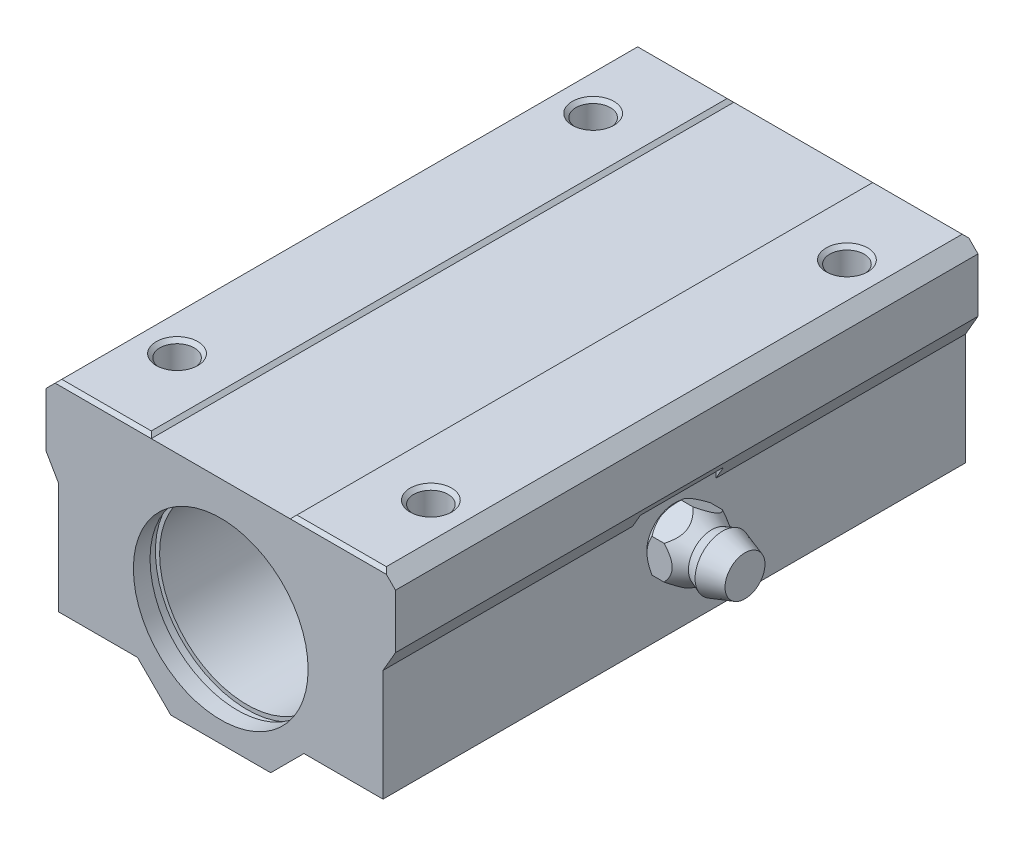
SolidWorks part; units mm, degrees
material "Plain Carbon Steel"
ref_plane "Front Plane" through (0, 0, 0) normal (0, 0, 1) x (1, 0, 0)
ref_plane "Top Plane" through (0, 0, 0) normal (0, 1, 0) x (1, 0, 0)
ref_plane "Right Plane" through (0, 0, 0) normal (1, 0, 0) x (0, 0, -1)
ref_plane "Plane1" through (0, 0, 0) normal (0, 0, 1) x (1, 0, 0)
sketch "Sketch1" plane through (0, 0, 0) normal (0, 0, 1) x (1, 0, 0)
  line L0 (-21, 12.5) -> (-21, 6)
  line L1 (-21, 6) -> (-19.5, 3.4019)
  line L2 (-19.5, 3.4019) -> (-19.5, -10)
  line L3 (-19.5, -10) -> (-10, -10)
  line L4 (-10, -10) -> (-6, -14)
  line L5 (-6, -14) -> (6, -14)
  line L6 (6, -14) -> (10, -10)
  line L7 (10, -10) -> (19.5, -10)
  line L8 (19.5, -10) -> (19.5, 3.4019)
  line L9 (19.5, 3.4019) -> (21, 6)
  line L10 (21, 6) -> (21, 12.5)
  line L11 (21, 12.5) -> (19.5, 14)
  line L12 (19.5, 14) -> (8.75, 14)
  line L13 (8.75, 14) -> (8.35, 13.6)
  line L14 (8.35, 13.6) -> (-8.35, 13.6)
  line L15 (-8.35, 13.6) -> (-8.75, 14)
  line L16 (-8.75, 14) -> (-19.5, 14)
  line L17 (-19.5, 14) -> (-21, 12.5)
extrude "Boss-Extrude1" add sketch "Sketch1" along normal blind 81
ref_plane "Plane2" through (0, 0, 0) normal (1, 0, 0) x (0, 0, -1)
sketch "Sketch2" plane through (0, 0, 0) normal (1, 0, 0) x (0, 0, -1)
  line L0 (-1497, -1094) -> (1434, -1094)
  line L1 (1434, -1094) -> (1434, 1075)
  line L2 (1434, 1075) -> (-1497, 1075)
  line L3 (-1497, 1075) -> (-1497, -1094)
  line L4 (-81, -14) -> (0, -14)
  line L5 (0, -14) -> (0, 13.6)
  line L6 (0, 13.6) -> (-0.4, 14)
  line L7 (-0.4, 14) -> (-80.6, 14)
  line L8 (-80.6, 14) -> (-81, 13.6)
  line L9 (-81, 13.6) -> (-81, -14)
extrude "Cut-Extrude1" cut sketch "Sketch2" against normal blind 42 and the other way blind 42
ref_plane "Plane3" through (0, 0, 15.5) normal (0, 0, 1) x (1, 0, 0)
sketch "Sketch3" plane through (0, 0, 15.5) normal (0, 0, 1) x (1, 0, 0)
  line L0 (-15.25, 14) -> (-12.75, 14)
  line L1 (-12.75, 14) -> (-13.183, 13.567)
  line L2 (-13.183, 13.567) -> (-13.183, 2)
  line L3 (-13.183, 2) -> (-13.1, 2)
  line L4 (-13.1, 2) -> (-13.1, -10)
  line L5 (-13.1, -10) -> (-15.25, -10)
  line L6 (-15.25, -10) -> (-15.25, 14)
  line L7 (-15.25, -10) -> (-15.25, 14) construction
revolve "Cut-Revolve1" cut sketch "Sketch3" angle 360 about L7
ref_plane "Plane4" through (0, 0, 15.5) normal (0, 0, 1) x (1, 0, 0)
sketch "Sketch4" plane through (0, 0, 15.5) normal (0, 0, 1) x (1, 0, 0)
  line L0 (15.25, 14) -> (17.75, 14)
  line L1 (17.75, 14) -> (17.317, 13.567)
  line L2 (17.317, 13.567) -> (17.317, 2)
  line L3 (17.317, 2) -> (17.4, 2)
  line L4 (17.4, 2) -> (17.4, -10)
  line L5 (17.4, -10) -> (15.25, -10)
  line L6 (15.25, -10) -> (15.25, 14)
  line L7 (15.25, -10) -> (15.25, 14) construction
revolve "Cut-Revolve2" cut sketch "Sketch4" angle 360 about L7
ref_plane "Plane5" through (0, 0, 65.5) normal (0, 0, 1) x (1, 0, 0)
sketch "Sketch5" plane through (0, 0, 65.5) normal (0, 0, 1) x (1, 0, 0)
  line L0 (-15.25, 14) -> (-12.75, 14)
  line L1 (-12.75, 14) -> (-13.183, 13.567)
  line L2 (-13.183, 13.567) -> (-13.183, 2)
  line L3 (-13.183, 2) -> (-13.1, 2)
  line L4 (-13.1, 2) -> (-13.1, -10)
  line L5 (-13.1, -10) -> (-15.25, -10)
  line L6 (-15.25, -10) -> (-15.25, 14)
  line L7 (-15.25, -10) -> (-15.25, 14) construction
revolve "Cut-Revolve3" cut sketch "Sketch5" angle 360 about L7
ref_plane "Plane6" through (0, 0, 65.5) normal (0, 0, 1) x (1, 0, 0)
sketch "Sketch6" plane through (0, 0, 65.5) normal (0, 0, 1) x (1, 0, 0)
  line L0 (15.25, 14) -> (17.75, 14)
  line L1 (17.75, 14) -> (17.317, 13.567)
  line L2 (17.317, 13.567) -> (17.317, 2)
  line L3 (17.317, 2) -> (17.4, 2)
  line L4 (17.4, 2) -> (17.4, -10)
  line L5 (17.4, -10) -> (15.25, -10)
  line L6 (15.25, -10) -> (15.25, 14)
  line L7 (15.25, -10) -> (15.25, 14) construction
revolve "Cut-Revolve4" cut sketch "Sketch6" angle 360 about L7
ref_plane "Plane7" through (0, 0, 0) normal (1, 0, 0) x (0, 0, -1)
sketch "Sketch7" plane through (0, 0, 0) normal (1, 0, 0) x (0, 0, -1)
  line L0 (-81, -1) -> (-81, 9.5)
  line L1 (-81, 9.5) -> (-73.5, 9.5)
  line L2 (-73.5, 9.5) -> (-73.5, 10)
  line L3 (-73.5, 10) -> (-72.35, 10)
  line L4 (-72.35, 10) -> (-72.35, 9.5)
  line L5 (-72.35, 9.5) -> (-8.65, 9.5)
  line L6 (-8.65, 9.5) -> (-8.65, 10)
  line L7 (-8.65, 10) -> (-7.5, 10)
  line L8 (-7.5, 10) -> (-7.5, 9.5)
  line L9 (-7.5, 9.5) -> (0, 9.5)
  line L10 (0, 9.5) -> (0, -1)
  line L11 (0, -1) -> (-81, -1)
  line L12 (0, -1) -> (-81, -1) construction
  line L13 (0, -10) -> (0, 3.4019) construction
  dimension "D1" = 8.65
  dimension "D2" = 7.5
  dimension "D3" = 7.5
  dimension "D4" = 8.65
  dimension "D5" = 0
revolve "Cut-Revolve5" cut sketch "Sketch7" angle 360 about L12
ref_plane "Plane8" through (0, 0, 40.5) normal (0, 0, 1) x (1, 0, 0)
sketch "Sketch8" plane through (0, 0, 40.5) normal (0, 0, 1) x (1, 0, 0)
  line L0 (19.5, 0) -> (19.5, 3.3)
  line L1 (19.5, 3.3) -> (20.5, 4.2)
  line L2 (20.5, 4.2) -> (21.5, 4.2)
  line L3 (21.5, 4.2) -> (24, 2.8)
  line L4 (24, 2.8) -> (25.3, 3.3)
  line L5 (25.3, 3.3) -> (28, 2.4)
  line L6 (28, 2.4) -> (28, 0)
  line L7 (28, 0) -> (19.5, 0)
  line L8 (28, 0) -> (19.5, 0) construction
revolve "Revolve1" add sketch "Sketch8" angle 360 about L8
ref_plane "Plane9" through (19.5, 0, 0) normal (1, 0, 0) x (0, 0, -1)
sketch "Sketch9" plane through (19.5, 0, 0) normal (1, 0, 0) x (0, 0, -1)
  line L0 (-45.5, -5) -> (-35.5, -5)
  line L1 (-35.5, -5) -> (-35.5, 5)
  line L2 (-35.5, 5) -> (-45.5, 5)
  line L3 (-45.5, 5) -> (-45.5, -5)
  line L4 (-44, 2.0207) -> (-44, -2.0207)
  line L5 (-44, -2.0207) -> (-40.5, -4.0415)
  line L6 (-40.5, -4.0415) -> (-37, -2.0207)
  line L7 (-37, -2.0207) -> (-37, 2.0207)
  line L8 (-37, 2.0207) -> (-40.5, 4.0415)
  line L9 (-40.5, 4.0415) -> (-44, 2.0207)
extrude "Cut-Extrude2" cut sketch "Sketch9" along normal blind 10
ref_plane "Plane10" through (0, 0, 40.5) normal (0, 0, 1) x (1, 0, 0)
sketch "Sketch10" plane through (0, 0, 40.5) normal (0, 0, 1) x (1, 0, 0)
  line L0 (19.5, 4.2) -> (19.5, 3.3)
  line L1 (19.5, 3.3) -> (20.5, 4.2)
  line L2 (20.5, 4.2) -> (19.5, 4.2)
  line L3 (28, 0) -> (19.5, 0) construction
revolve "Cut-Revolve6" cut sketch "Sketch10" angle 360 about L3
sketch "Sketch11" plane through (0, 14, 0) normal (0, 1, 0) x (1, 0, 0)
  line L1 (-38.8037, -75.5) -> (62.903, -75.5)
  line L2 (-38.8037, -75.5) -> (-38.8037, -5.5)
  line L3 (-38.8037, -5.5) -> (62.903, -5.5)
  line L4 (62.903, -75.5) -> (62.903, -5.5)
  line L5 (-38.8037, -75.5) -> (62.903, -5.5) construction
  line L6 (-38.8037, -5.5) -> (62.903, -75.5) construction
  line L7 (-107.2614, 66.1524) -> (131.3607, 66.1524)
  line L8 (-107.2614, 66.1524) -> (-107.2614, -147.1524)
  line L9 (-107.2614, -147.1524) -> (131.3607, -147.1524)
  line L10 (131.3607, 66.1524) -> (131.3607, -147.1524)
  line L11 (-107.2614, 66.1524) -> (131.3607, -147.1524) construction
  line L12 (-107.2614, -147.1524) -> (131.3607, 66.1524) construction
  point P0 (12.0496, -40.5)
  point P5 (12.0496, -40.5)
  dimension "D1" = 70
extrude "Cut-Extrude3" cut sketch "Sketch11" against normal up to next
chamfer "Chamfer1" distance 0.4 angle 45 4 edges at (-14.125, 14, 5.5) (14.125, 14, 5.5) (14.125, 14, 75.5) (-14.125, 14, 75.5)
